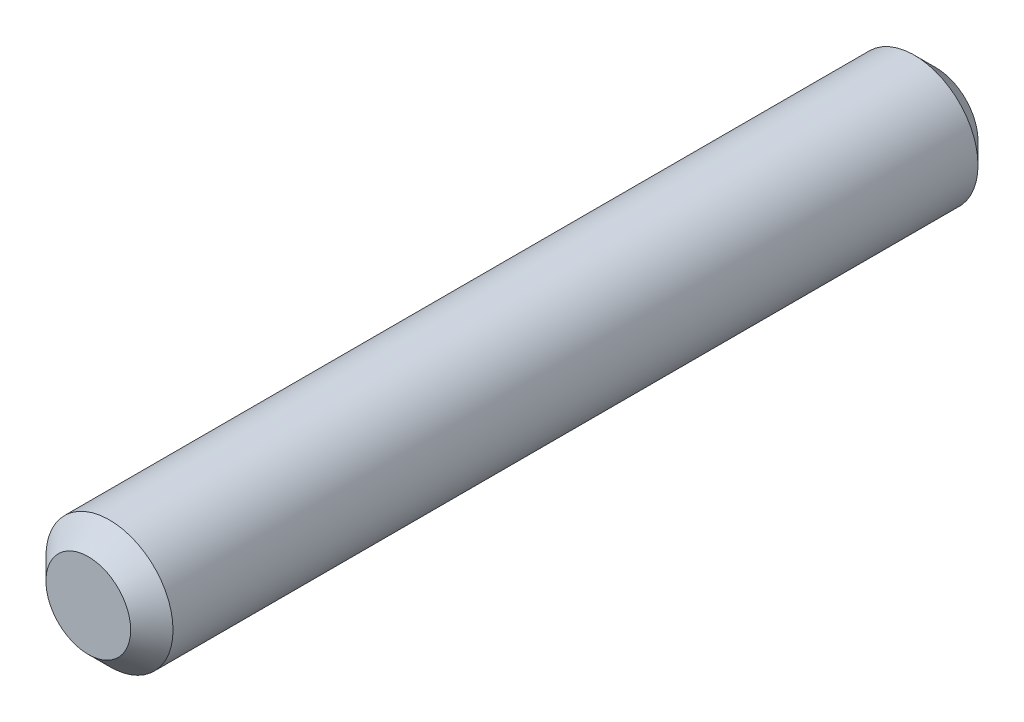
SolidWorks part; units mm, degrees
material "SUS304"
ref_plane "前视基准面" through (0, 0, 0) normal (0, 0, 1) x (1, 0, 0)
ref_plane "上视基准面" through (0, 0, 0) normal (0, 1, 0) x (1, 0, 0)
ref_plane "右视基准面" through (0, 0, 0) normal (1, 0, 0) x (0, 0, -1)
sketch "草图1" plane through (0, 0, 0) normal (0, 0, 1) x (1, 0, 0)
  circle A0 centre (0, 0) radius 1.5
  dimension "D1" = 3
extrude "拉伸1" add sketch "草图1" along normal mid plane 20
chamfer "倒角1" distance 0.5 angle 45 2 edges at (1.5, 0, -10) (1.5, 0, 10)
